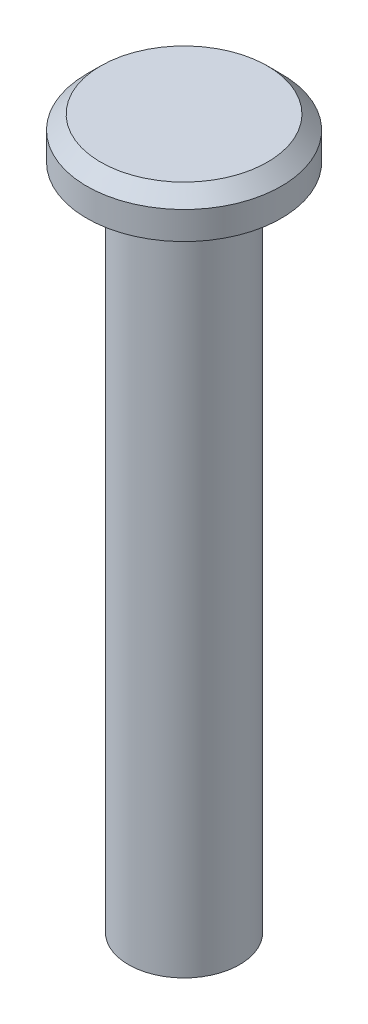
SolidWorks part; units mm, degrees
ref_plane "Front Plane" through (0, 0, 0) normal (0, 0, 1) x (1, 0, 0)
ref_plane "Top Plane" through (0, 0, 0) normal (0, 1, 0) x (1, 0, 0)
ref_plane "Right Plane" through (0, 0, 0) normal (1, 0, 0) x (0, 0, -1)
sketch "Sketch1" plane through (0, 0, 0) normal (0, 0, 1) x (1, 0, 0)
  line L0 (0, 0) -> (4, 0)
  line L1 (4, 0) -> (4, 48)
  line L2 (4, 48) -> (7, 48)
  line L3 (7, 48) -> (7, 50)
  line L4 (6, 51) -> (0, 51)
  line L5 (0, 51) -> (0, 0)
  line L6 (0, 33.605) -> (0, -11.1185) construction
  line L7 (7, 50) -> (6, 51)
  point P6 (7, 51)
  dimension "D1" = 8
  dimension "D2" = 48
  dimension "D3" = 3
  dimension "D4" = 14
revolve "Revolve1" add sketch "Sketch1" angle 360 about L6
cosmetic thread "Cosmetic Thread2" parameters "D1"=3, "D2"=6.561
